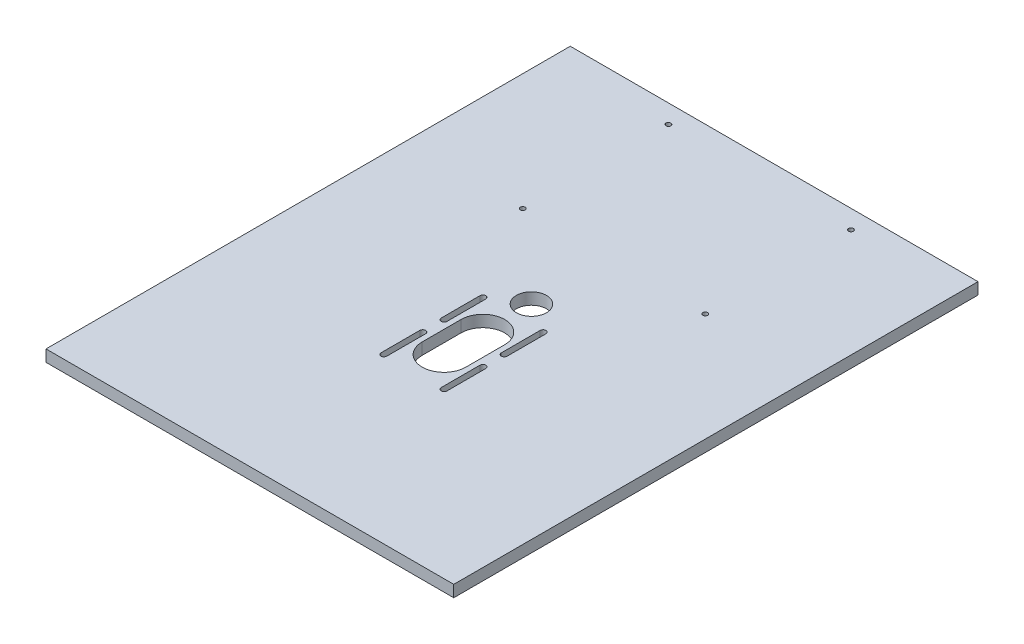
SolidWorks part; units mm, degrees
ref_plane "Front Plane" through (0, 0, 0) normal (0, 0, 1) x (1, 0, 0)
ref_plane "Top Plane" through (0, 0, 0) normal (0, 1, 0) x (1, 0, 0)
ref_plane "Right Plane" through (0, 0, 0) normal (1, 0, 0) x (0, 0, -1)
sketch "Sketch1" plane through (0, 0, 0) normal (0, 1, 0) x (1, 0, 0)
  line L4 (-105, -145) -> (105, -145)
  line L5 (105, -145) -> (105, 125)
  line L6 (105, 125) -> (-105, 125)
  line L7 (-105, 125) -> (-105, -145)
  circle A1 centre (0, 0) radius 7.75
extrude "Boss-Extrude2" add sketch "Sketch1" along normal blind 6
sketch "Sketch3" plane through (0, 0, 0) normal (0, -1, 0) x (1, 0, 0)
  line L0 (0, 0) -> (0, 45) construction
  line L1 (15.5, 29.5) -> (15.5, 9.5) construction
  line L2 (15.5, 29.5) -> (-15.5, 29.5) construction
  line L3 (15.5, 29.5) -> (15.5, 60.5) construction
  line L4 (15.5, 60.5) -> (-15.5, 60.5) construction
  line L5 (-15.5, 29.5) -> (-15.5, 60.5) construction
  line L6 (15.5, 29.5) -> (-15.5, 60.5) construction
  line L7 (15.5, 60.5) -> (-15.5, 29.5) construction
  line L8 (17, 29.5) -> (17, 9.5)
  line L9 (14, 29.5) -> (14, 9.5)
  line L10 (15.5, 60.5) -> (15.5, 40.5) construction
  line L11 (17, 60.5) -> (17, 40.5)
  line L12 (14, 60.5) -> (14, 40.5)
  line L13 (-15.5, 29.5) -> (-15.5, 9.5) construction
  line L14 (-17, 29.5) -> (-17, 9.5)
  line L15 (-14, 29.5) -> (-14, 9.5)
  line L16 (-15.5, 60.5) -> (-15.5, 40.5) construction
  line L17 (-17, 60.5) -> (-17, 40.5)
  line L18 (-14, 60.5) -> (-14, 40.5)
  line L19 (0, 45) -> (0, 25) construction
  line L20 (11.25, 45) -> (11.25, 25)
  line L21 (-11.25, 45) -> (-11.25, 25)
  circle A0 centre (0, 45) radius 11.25 construction
  arc A1 (17, 29.5) -> (14, 29.5) centre (15.5, 29.5) ccw
  arc A2 (14, 9.5) -> (17, 9.5) centre (15.5, 9.5) ccw
  arc A3 (17, 60.5) -> (14, 60.5) centre (15.5, 60.5) ccw
  arc A4 (14, 40.5) -> (17, 40.5) centre (15.5, 40.5) ccw
  arc A5 (-17, 29.5) -> (-14, 29.5) centre (-15.5, 29.5) cw
  arc A6 (-14, 9.5) -> (-17, 9.5) centre (-15.5, 9.5) cw
  arc A7 (-17, 60.5) -> (-14, 60.5) centre (-15.5, 60.5) cw
  arc A8 (-14, 40.5) -> (-17, 40.5) centre (-15.5, 40.5) cw
  arc A9 (11.25, 45) -> (-11.25, 45) centre (0, 45) ccw
  arc A10 (-11.25, 25) -> (11.25, 25) centre (0, 25) ccw
  point P9 (15.5, 19.5)
  point P15 (15.5, 50.5)
  point P23 (-15.5, 19.5)
  point P30 (-15.5, 50.5)
  point P36 (0, 35)
  dimension "D1" = 31
  dimension "D3" = 22.5
  dimension "D5" = 1.5
  dimension "D6" = 1.5
  dimension "D9" = 11.25
  dimension "D2" = 31
  dimension "D4" = 20
  dimension "D7" = 20
  dimension "D8" = 20
extrude "Cut-Extrude1" cut sketch "Sketch3" against normal blind 10
sketch "Sketch4" plane through (0, 0, 0) normal (0, -1, 0) x (1, 0, 0)
  circle A0 centre (49.1703, -115.3822) radius 1.25
  circle A1 centre (-44.8297, -115.3822) radius 1.25
  circle A2 centre (49.1703, -40.3822) radius 1.25
  circle A3 centre (-44.8297, -40.3822) radius 1.25
  dimension "D1" = 2.5
extrude "Cut-Extrude2" cut sketch "Sketch4" against normal blind 10
